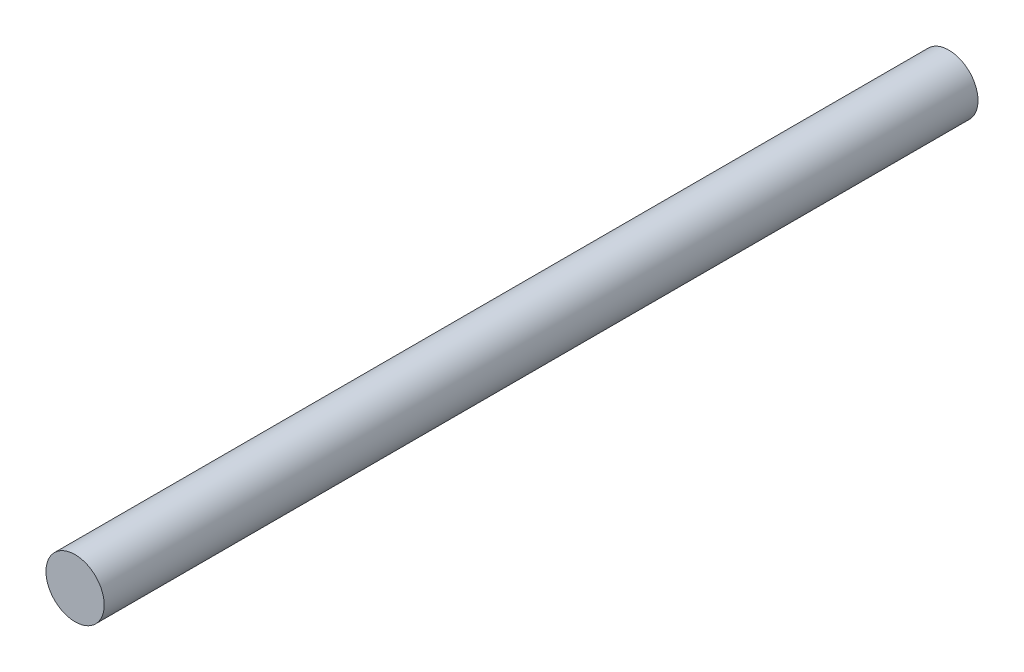
SolidWorks part; units mm, degrees
ref_plane "Front Plane" through (0, 0, 0) normal (0, 0, 1) x (1, 0, 0)
ref_plane "Top Plane" through (0, 0, 0) normal (0, 1, 0) x (1, 0, 0)
ref_plane "Right Plane" through (0, 0, 0) normal (1, 0, 0) x (0, 0, -1)
sketch "Sketch1" plane through (0, 0, 0) normal (0, 0, 1) x (1, 0, 0)
  circle A0 centre (0, 0) radius 50
  dimension "D1" = 100
extrude "Boss-Extrude1" add sketch "Sketch1" along normal blind 1500
